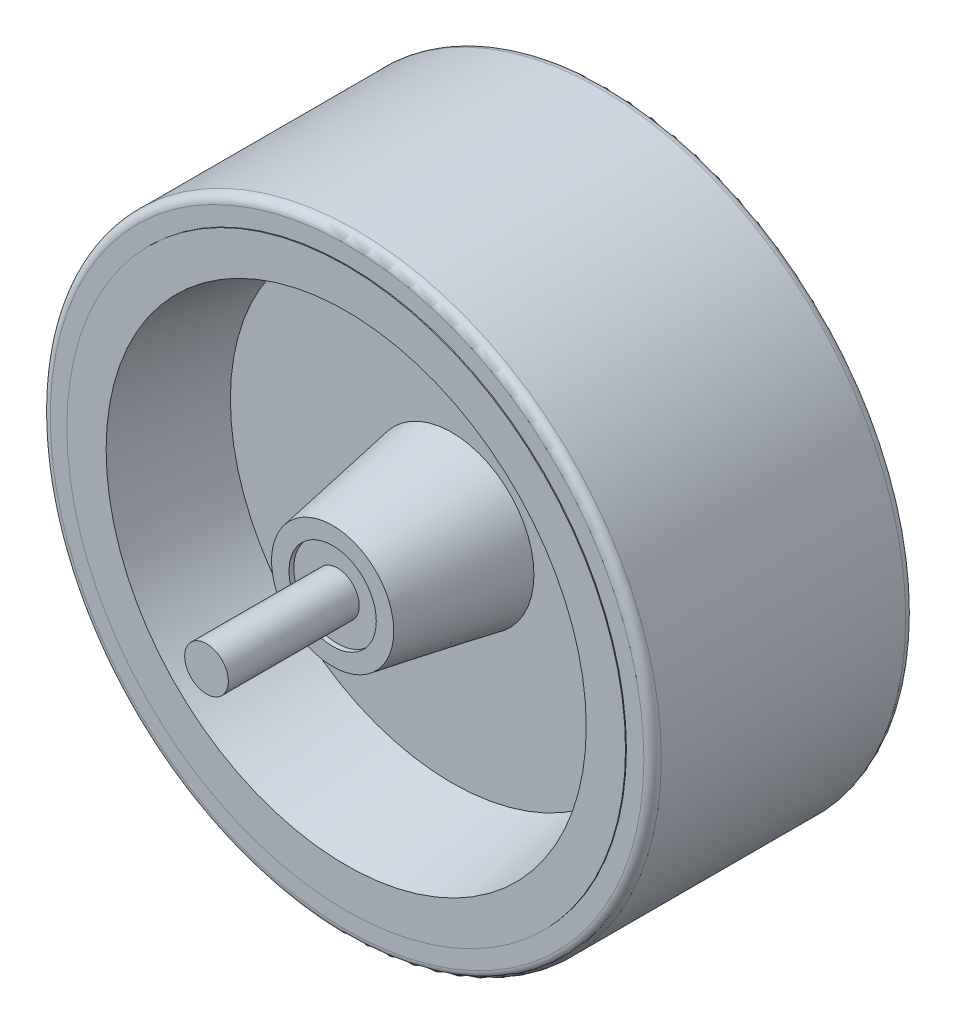
SolidWorks part; units mm, degrees
ref_plane "Front Plane" through (0, 0, 0) normal (0, 0, 1) x (1, 0, 0)
ref_plane "Top Plane" through (0, 0, 0) normal (0, 1, 0) x (1, 0, 0)
ref_plane "Right Plane" through (0, 0, 0) normal (1, 0, 0) x (0, 0, -1)
sketch "Sketch1" plane through (0, 0, 0) normal (0, 0, 1) x (1, 0, 0)
  circle A0 centre (0, 0) radius 88.9
  circle A1 centre (0, 0) radius 78.74
  dimension "D1" = 177.8
  dimension "D2" = 10.16
extrude "Boss-Extrude1" add sketch "Sketch1" along normal mid plane 76.2
fillet "Fillet1" radius 2.54 2 edges at (88.9, 0, -38.1) (88.9, 0, 38.1)
sketch "Sketch3" plane through (0, 0, 0) normal (0, 1, 0) x (1, 0, 0)
  line L0 (0, 0) -> (0, 60.9728) construction
  line L1 (0, 0) -> (-137.1098, 0) construction
  line L2 (0, 40.894) -> (0, -40.894)
  line L3 (0, -40.894) -> (-12.7, -40.894)
  line L4 (-12.7, -40.894) -> (-12.7, -42.291)
  line L5 (-12.7, -42.291) -> (-17.78, -42.291)
  line L6 (-17.78, -42.291) -> (-23.8934, -7.62)
  line L7 (-23.8934, -7.62) -> (-64.4308, -7.62)
  line L8 (-64.4308, -7.62) -> (-69.85, -38.354)
  line L9 (-69.85, -38.354) -> (-81.28, -38.354)
  line L10 (-81.28, -38.354) -> (-81.28, 38.354)
  line L11 (-12.7, 40.894) -> (-12.7, 42.291)
  line L12 (0, 40.894) -> (-12.7, 40.894)
  line L13 (-12.7, 42.291) -> (-17.78, 42.291)
  line L14 (-69.85, 38.354) -> (-81.28, 38.354)
  line L15 (-64.4308, 7.62) -> (-69.85, 38.354)
  line L16 (-23.8934, 7.62) -> (-64.4308, 7.62)
  line L17 (-17.78, 42.291) -> (-23.8934, 7.62)
  point P21 (-81.28, 0)
  dimension "D1" = 40.894
  dimension "D2" = 12.7
  dimension "D3" = 1.397
  dimension "D4" = 5.08
  dimension "D5" = 100
  dimension "D6" = 100
  dimension "D7" = 38.354
  dimension "D8" = 11.43
  dimension "D9" = 81.28
  dimension "D10" = 7.62
revolve "Revolve1" add sketch "Sketch3" angle 360 about L0
sketch "Sketch8" plane through (0, 0, 40.894) normal (0, 0, 1) x (1, 0, 0)
  circle A0 centre (0, 0) radius 6.35
  dimension "D1" = 12.7
extrude "Boss-Extrude2" add sketch "Sketch8" along normal blind 38.1
sketch "Sketch11" plane through (0, 0, -40.894) normal (0, 0, -1) x (-1, 0, 0)
  circle A0 centre (0, 0) radius 6.35
  dimension "D1" = 12.7
extrude "Boss-Extrude3" add sketch "Sketch11" along normal blind 38.1
